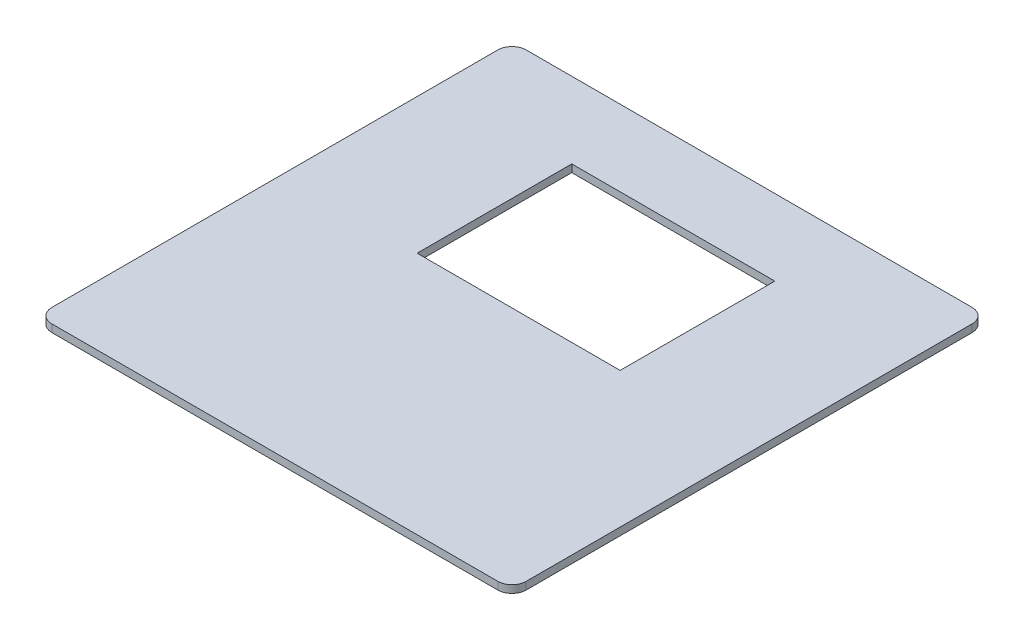
SolidWorks part; units mm, degrees
ref_plane "Front Plane" through (0, 0, 0) normal (0, 0, 1) x (1, 0, 0)
ref_plane "Top Plane" through (0, 0, 0) normal (0, 1, 0) x (1, 0, 0)
ref_plane "Right Plane" through (0, 0, 0) normal (1, 0, 0) x (0, 0, -1)
sketch "Sketch1" plane through (0, 2.62, 0) normal (0, 1, 0) x (1, 0, 0)
  line L0 (-66.8334, 40.3361) -> (-66.8334, -59.6639) construction
  line L1 (-116.8334, 40.3361) -> (-16.8334, 40.3361)
  line L2 (-116.8334, 40.3361) -> (-116.8334, -59.6639)
  line L3 (-116.8334, -59.6639) -> (-16.8334, -59.6639)
  line L4 (-88.2334, 24.3361) -> (-88.2334, -8.2639)
  line L5 (-88.2334, -8.2639) -> (-45.4334, -8.2639)
  line L6 (-45.4334, -8.2639) -> (-45.4334, 24.3361)
  line L7 (-45.4334, 24.3361) -> (-88.2334, 24.3361)
  line L8 (-88.2334, 24.3361) -> (-88.2334, -8.2639)
  line L9 (-88.2334, -8.2639) -> (-45.4334, -8.2639)
  line L10 (-45.4334, -8.2639) -> (-45.4334, 24.3361)
  line L11 (-45.4334, 24.3361) -> (-88.2334, 24.3361)
  line L12 (-16.8334, 40.3361) -> (-16.8334, -59.6639)
  dimension "D2" = 16
  dimension "D3" = 100
  dimension "D4" = 100
  dimension "D1" = 0
extrude "Boss-Extrude1" add sketch "Sketch1" along normal blind 1.6
fillet "Fillet1" radius 3 4 edges at (-16.8334, 3.42, 59.6639) (-116.8334, 3.42, 59.6639) (-116.8334, 3.42, -40.3361) (-16.8334, 3.42, -40.3361)
